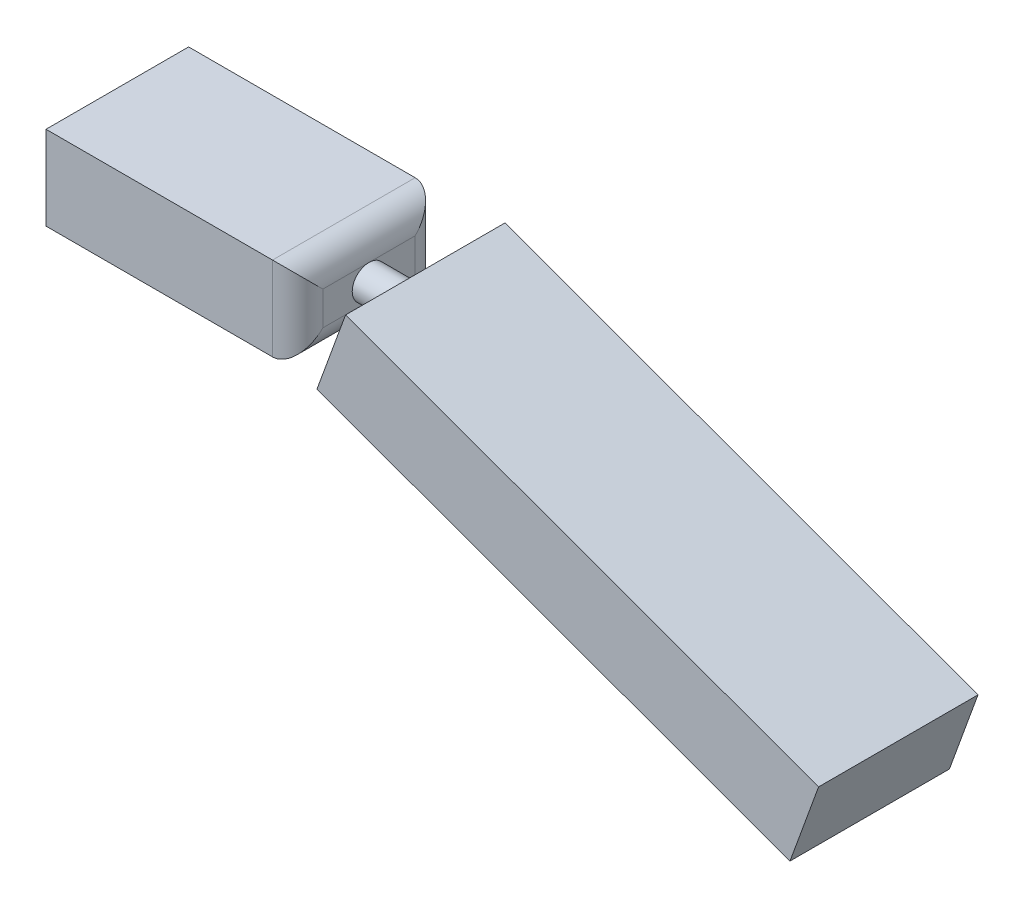
SolidWorks part; units mm, degrees
ref_plane "前视基准面" through (0, 0, 0) normal (0, 0, 1) x (1, 0, 0)
ref_plane "上视基准面" through (0, 0, 0) normal (0, 1, 0) x (1, 0, 0)
ref_plane "右视基准面" through (0, 0, 0) normal (1, 0, 0) x (0, 0, -1)
sketch "草图1" plane through (0, 0, 0) normal (0, 1, 0) x (1, 0, 0)
  line L1 (0, 0) -> (30, 0)
  line L2 (0, 0) -> (0, 17)
  line L3 (0, 17) -> (30, 17)
  line L4 (30, 0) -> (30, 17)
  dimension "D1" = 30
  dimension "D2" = 17
extrude "凸台-拉伸1" add sketch "草图1" along normal blind 10
sketch "草图2" plane through (0, 0, 0) normal (-1, 0, 0) x (0, 0, 1)
  line L0 (-17, 5) -> (0, 5) construction
  line L1 (-17, 10) -> (-17, 0) construction
  line L2 (0, 10) -> (0, 0) construction
  line L3 (-15.5, 1.5) -> (-15.5, 8.5)
  line L4 (-15.5, 8.5) -> (-1.5, 8.5)
  line L5 (-1.5, 8.5) -> (-1.5, 1.5)
  line L6 (-15.5, 1.5) -> (-1.5, 1.5)
  point P11 (-1.5, 5)
  point P12 (-15.5, 5)
  dimension "D1" = 14
  dimension "D2" = 3.5
  dimension "D3" = 1.5
extrude "切除-拉伸1" cut sketch "草图2" against normal blind 12
fillet "圆角1" radius 3 4 edges at (30, 5, 0) (30, 10, -8.5) (30, 5, -17) (30, 0, -8.5)
sketch "草图4" plane through (30, 0, 0) normal (1, 0, 0) x (0, 0, -1)
  line L0 (8.5, 7) -> (8.5, 3) construction
  line L1 (14, 7) -> (3, 7) construction
  line L2 (3, 3) -> (14, 3) construction
  circle A0 centre (8.5, 5) radius 2
extrude "凸台-拉伸2" add sketch "草图4" along normal blind 5
sketch "草图5" plane through (0, 0, 0) normal (0, 0, 1) x (1, 0, 0)
  line L0 (35, 5) -> (55.3655, -2.4125) construction
  line L1 (35, 3) -> (35, 7) construction
  line L2 (36.7045, 9.6832) -> (33.2955, 0.3168)
  line L3 (33.2955, 0.3168) -> (89.677, -20.2044)
  line L4 (89.677, -20.2044) -> (93.0861, -10.838)
  line L5 (36.7045, 9.6832) -> (93.0861, -10.838)
  line L6 (35, 5) -> (22.0911, 5) construction
  point P9 (91.3816, -15.5212)
  dimension "D1" = 60
  dimension "D2" = 160
extrude "凸台-拉伸3" add sketch "草图5" against normal blind 18 and the other way blind 1
